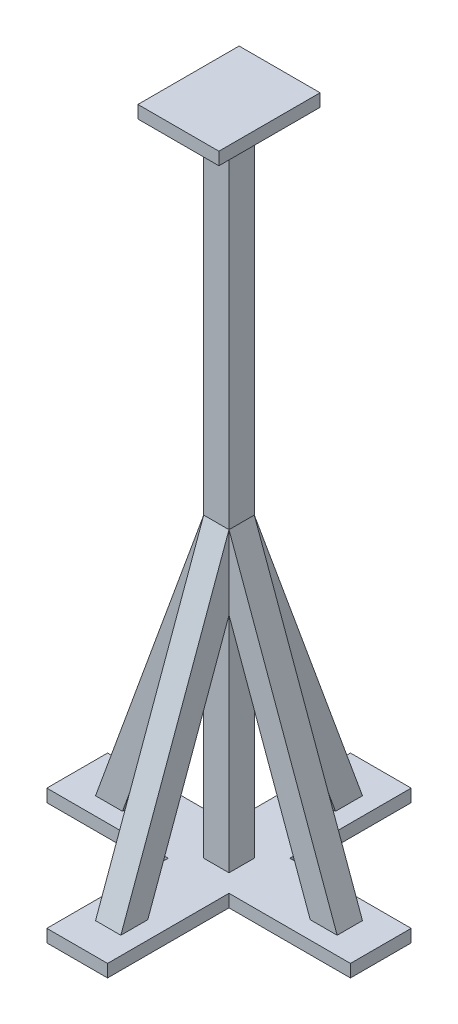
SolidWorks part; units mm, degrees
ref_plane "Front Plane" through (0, 0, 0) normal (0, 0, 1) x (1, 0, 0)
ref_plane "Top Plane" through (0, 0, 0) normal (0, 1, 0) x (1, 0, 0)
ref_plane "Right Plane" through (0, 0, 0) normal (1, 0, 0) x (0, 0, -1)
sketch "Sketch2" plane through (0, 0, 0) normal (0, 1, 0) x (1, 0, 0)
  line L0 (0, -1054) -> (0, -300) construction
  line L1 (-300, 60) -> (-60, 60)
  line L2 (-300, 60) -> (-300, -60)
  line L3 (-300, -60) -> (-60, -60)
  line L4 (300, 60) -> (300, -60)
  line L5 (-60, 300) -> (60, 300)
  line L6 (-60, 300) -> (-60, 60)
  line L7 (-60, -300) -> (60, -300)
  line L8 (60, 300) -> (60, 60)
  line L9 (-1066.0925, 0) -> (-300, 0) construction
  line L10 (-60, -60) -> (-60, -300)
  line L11 (300, 0) -> (3.429, 0) construction
  line L12 (60, 60) -> (300, 60)
  line L13 (0, 300) -> (0, -12.025) construction
  line L14 (60, -60) -> (60, -300)
  line L15 (60, -60) -> (300, -60)
  point P16 (-3.0934, 8.8781)
  dimension "D1" = 600
  dimension "D2" = 120
  dimension "D3" = 60
  dimension "D4" = 60
extrude "Boss-Extrude1" add sketch "Sketch2" along normal blind 25
sketch "Sketch3" plane through (0, 0, 0) normal (0, -1, 0) x (1, 0, 0)
  line L1 (-25, -25) -> (25, -25)
  line L2 (-25, -25) -> (-25, 25)
  line L3 (-25, 25) -> (25, 25)
  line L4 (25, -25) -> (25, 25)
  dimension "D1" = 50
  dimension "D2" = 50
  dimension "D3" = 25
  dimension "D4" = 25
extrude "Boss-Extrude2" add sketch "Sketch3" against normal blind 1300
sketch "Sketch4" plane through (0, 0, 0) normal (0, -1, 0) x (1, 0, 0)
  line L4 (60, 300) -> (60, 60) construction
  line L5 (-273.5654, -12.5) -> (-188.5654, -12.5)
  line L6 (-188.5654, -12.5) -> (-188.5654, 12.5)
  line L7 (-42.5, 255) -> (42.5, 255)
  line L8 (42.5, 255) -> (42.5, 280)
  line L9 (-188.5654, 12.5) -> (-273.5654, 12.5)
  line L10 (-273.5654, 12.5) -> (-273.5654, -12.5)
  line L11 (-470.2813, 0) -> (585.0329, 0) construction
  line L12 (-42.5, -280) -> (42.5, -280)
  line L13 (42.5, -280) -> (42.5, -255)
  line L14 (42.5, -255) -> (-42.5, -255)
  line L15 (-42.5, -255) -> (-42.5, -280)
  line L16 (179.6305, -12.5) -> (264.6305, -12.5)
  line L17 (60, -300) -> (-60, -300) construction
  line L18 (264.6305, -12.5) -> (264.6305, 12.5)
  line L19 (264.6305, 12.5) -> (179.6305, 12.5)
  line L20 (179.6305, 12.5) -> (179.6305, -12.5)
  line L21 (-273.5654, -12.5) -> (-188.5654, 12.5) construction
  line L22 (-60, -280) -> (-42.5, -280)
  line L23 (-60, -300) -> (-60, -60) construction
  line L24 (42.5, -255) -> (60, -255)
  line L25 (60, -60) -> (60, -300) construction
  line L26 (42.5, 280) -> (-42.5, 280)
  line L27 (-42.5, 280) -> (-42.5, 255)
  line L28 (-60, 255) -> (-42.5, 255)
  line L29 (42.5, 280) -> (60, 280)
  line L30 (-60, 60) -> (-60, 300) construction
  line L31 (-60, 300) -> (60, 300) construction
  line L32 (264.6305, -12.5) -> (179.6305, 12.5) construction
  line L33 (-42.5, 255) -> (42.5, 280) construction
  line L34 (42.5, 255) -> (-42.5, 280) construction
  line L35 (-42.5, -255) -> (42.5, -280) construction
  line L36 (-42.5, -280) -> (42.5, -255) construction
  line L37 (179.6305, -12.5) -> (264.6305, 12.5) construction
  circle A0 centre (0, 0) radius 267.5 construction
  point P22 (57.3758, 0)
  dimension "D1" = 85
  dimension "D2" = 25
  dimension "D3" = 20
  dimension "D4" = 85
  dimension "D5" = 20
  dimension "D6" = 85
  dimension "D7" = 25
  dimension "D8" = 25
  dimension "D9" = 57.3758
sketch "Sketch5" plane through (0, 0, 25) normal (0, 0, 1) x (1, 0, 0)
  line L0 (25, 466.0516) -> (185.5296, 25)
  line L1 (25, 1300) -> (25, 25) construction
  line L2 (60, 25) -> (300, 25) construction
  line L3 (185.5296, 25) -> (238.7385, 25)
  line L4 (238.7385, 25) -> (25, 612.2418)
  line L5 (25, 1300) -> (25, 25) construction
  line L6 (25, 612.2418) -> (25, 466.0516)
  point P6 (209.8459, 25)
  point P11 (302.5009, 25)
  point P12 (0, 0)
  point P13 (228.4493, 25)
  dimension "D1" = 50
  dimension "70" = 70
extrude "Boss-Extrude3" add sketch "Sketch5" against normal blind 50 separate body
sketch "Sketch6" plane through (0, 0, 0) normal (1, 0, 0) x (0, 0, -1)
  line L0 (0, 0) -> (0, 1355.4371) construction
pattern_circular "CirPattern1" count 4 every 90 about axis through (0, 0, 0) along (0, 1, 0) of bodies 103
sketch "Sketch7" plane through (0, 1300, 0) normal (0, 1, 0) x (1, 0, 0)
  line L0 (0, 0) -> (0, 100) construction
  line L1 (-80, 100) -> (80, 100)
  line L2 (-80, 100) -> (-80, -100)
  line L3 (-80, -100) -> (80, -100)
  line L4 (80, 100) -> (80, -100)
  line L5 (0, 0) -> (-80, 0) construction
  line L6 (-470.2813, 0) -> (585.0329, 0) construction
  dimension "D1" = 160
  dimension "D2" = 200
extrude "Boss-Extrude4" add sketch "Sketch7" along normal blind 25
